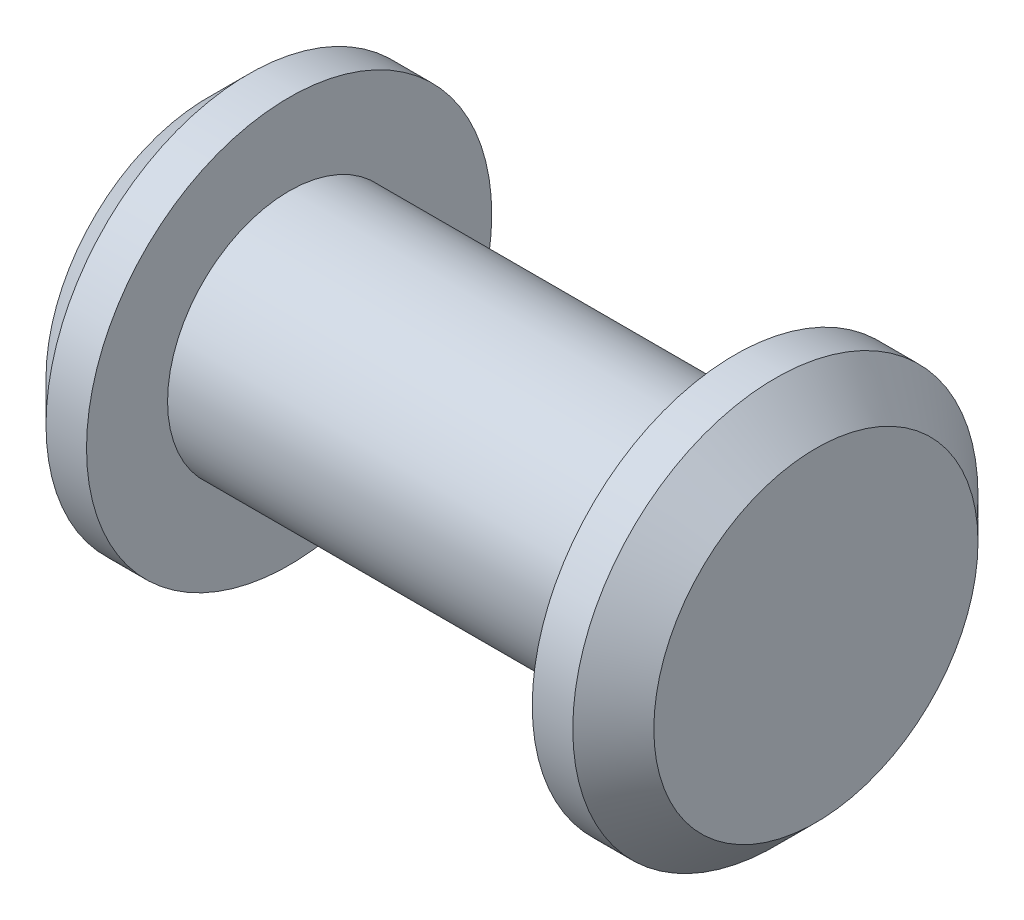
SolidWorks part; units mm, degrees
ref_plane "Front Plane" through (0, 0, 0) normal (0, 0, 1) x (1, 0, 0)
ref_plane "Top Plane" through (0, 0, 0) normal (0, 1, 0) x (1, 0, 0)
ref_plane "Right Plane" through (0, 0, 0) normal (1, 0, 0) x (0, 0, -1)
sketch "Sketch1" plane through (0, 0, 0) normal (0, 0, 1) x (1, 0, 0)
  line L0 (0, 0) -> (10722.7901, 0) construction
  line L1 (0, 0) -> (0, -10722.7901) construction
  line L2 (-15, 0) -> (-15, 8)
  line L3 (-13, 10) -> (-11, 10)
  line L4 (-11, 10) -> (-11, 6)
  line L5 (-11, 6) -> (11, 6)
  line L6 (11, 10) -> (11, 6)
  line L7 (13, 10) -> (11, 10)
  line L8 (15, 0) -> (15, 8)
  line L9 (-15, 8) -> (-13, 10)
  line L10 (15, 8) -> (13, 10)
  line L11 (-15, 0) -> (15, 0)
  point P6 (-15, 10)
  point P12 (0, 6)
  point P13 (15, 10)
  point P18 (0, 0)
  dimension "D1" = 2
  dimension "D2" = 12
  dimension "D3" = 4
  dimension "D4" = 11
  dimension "D5" = 45
  dimension "D6" = 2
  dimension "D7" = 45
  dimension "D8" = 20
revolve "Revolve1" add sketch "Sketch1" angle 360 about L11
